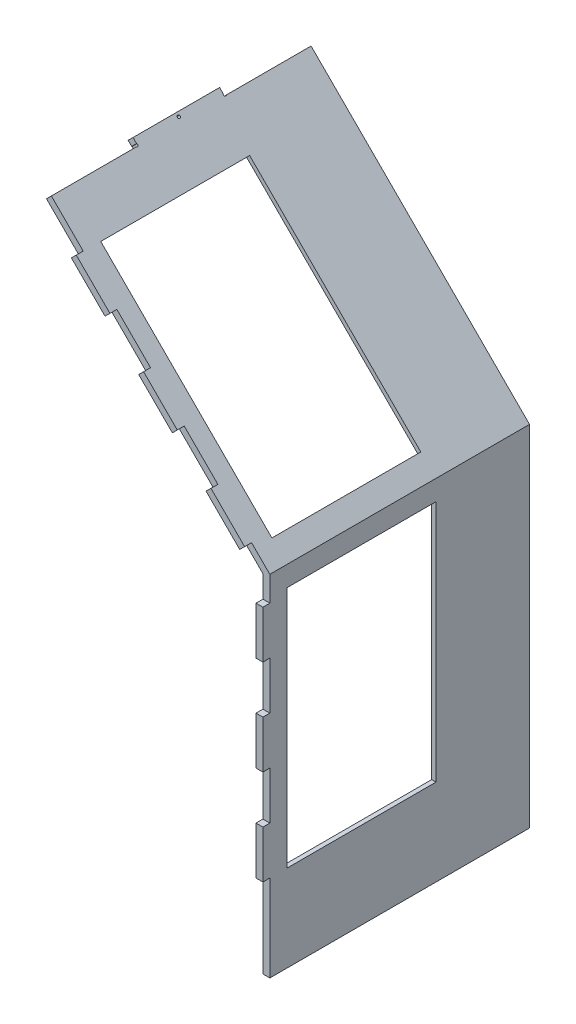
SolidWorks part; units mm, degrees
ref_plane "Plan de face" through (0, 0, 0) normal (0, 0, 1) x (1, 0, 0)
ref_plane "Plan de dessus" through (0, 0, 0) normal (0, 1, 0) x (1, 0, 0)
ref_plane "Plan de droite" through (0, 0, 0) normal (1, 0, 0) x (0, 0, -1)
sketch "Esquisse1" plane through (0, 0, 0) normal (0, 0, 1) x (1, 0, 0)
  line L0 (-190.432, 361.9326) -> (-44.5761, 361.9326) construction
  line L1 (-49.9708, -41.9174) -> (-57.9708, -41.9174)
  line L2 (-313.6277, 614.2758) -> (-307.9708, 619.9326)
  line L3 (-71.4129, -41.9174) -> (-190.432, -41.9174) construction
  line L4 (-57.9708, -41.9174) -> (-57.9708, 358.6189)
  line L6 (-57.9708, 358.6189) -> (-313.6277, 614.2758)
  line L11 (-49.9708, -41.9174) -> (-49.9708, 361.9326)
  line L13 (-49.9708, 361.9326) -> (-307.9708, 619.9326)
  dimension "D1" = 135
  dimension "D2" = 403.85
  dimension "D4" = 8
  dimension "D5" = 8
extrude "Boss.-Extru.1" add sketch "Esquisse1" along normal blind 308
sketch "Esquisse2" plane through (0, 0, 308) normal (0, 0, 1) x (1, 0, 0)
  line L0 (-57.9708, 358.6189) -> (-57.9708, -41.9174) construction
  line L1 (-57.9708, 58.0826) -> (-49.9708, 58.0826)
  line L2 (-57.9708, 58.0826) -> (-57.9708, -41.9174)
  line L3 (-57.9708, -41.9174) -> (-49.9708, -41.9174)
  line L4 (-49.9708, 58.0826) -> (-49.9708, -41.9174)
  line L5 (-57.9708, 223.0826) -> (-49.9708, 223.0826) construction
  line L6 (-49.9708, -41.9174) -> (-49.9708, 361.9326) construction
  line L7 (-57.9708, 168.0826) -> (-49.9708, 168.0826) construction
  line L8 (-57.9708, 278.0826) -> (-49.9708, 278.0826) construction
  line L9 (-57.9708, 333.0826) -> (-49.9708, 333.0826) construction
  line L10 (-57.9708, 113.0826) -> (-49.9708, 113.0826) construction
  line L11 (-271.2013, 571.8494) -> (-265.5444, 577.5062)
  line L12 (-57.9708, 168.0826) -> (-49.9708, 168.0826)
  line L13 (-57.9708, 168.0826) -> (-57.9708, 113.0826)
  line L14 (-57.9708, 113.0826) -> (-49.9708, 113.0826)
  line L15 (-49.9708, 168.0826) -> (-49.9708, 113.0826)
  line L16 (-57.9708, 278.0826) -> (-49.9708, 278.0826)
  line L17 (-57.9708, 278.0826) -> (-57.9708, 223.0826)
  line L18 (-57.9708, 223.0826) -> (-49.9708, 223.0826)
  line L19 (-49.9708, 278.0826) -> (-49.9708, 223.0826)
  line L21 (-313.6277, 614.2758) -> (-57.9708, 358.6189) construction
  line L23 (-232.3104, 532.9585) -> (-226.6535, 538.6153)
  line L24 (-193.4195, 494.0676) -> (-187.7627, 499.7245)
  line L25 (-154.5286, 455.1767) -> (-148.8718, 460.8336)
  line L26 (-115.6378, 416.2859) -> (-109.9809, 421.9427)
  line L27 (-76.7469, 377.395) -> (-71.09, 383.0518)
  line L28 (-307.9708, 619.9326) -> (-313.6277, 614.2758) construction
  line L29 (-49.9708, 361.9326) -> (-307.9708, 619.9326) construction
  line L30 (-271.2013, 571.8494) -> (-313.6277, 614.2758)
  line L31 (-313.6277, 614.2758) -> (-307.9708, 619.9326)
  line L32 (-307.9708, 619.9326) -> (-265.5444, 577.5062)
  line L33 (-193.4195, 494.0676) -> (-232.3104, 532.9585)
  line L34 (-226.6535, 538.6153) -> (-187.7627, 499.7245)
  line L35 (-154.5286, 455.1767) -> (-115.6378, 416.2859)
  line L36 (-148.8718, 460.8336) -> (-109.9809, 421.9427)
  line L37 (-76.7469, 377.395) -> (-57.9708, 358.6189)
  line L38 (-57.9708, 358.6189) -> (-57.9708, 333.0826)
  line L39 (-57.9708, 333.0826) -> (-49.9708, 333.0826)
  line L40 (-49.9708, 333.0826) -> (-49.9708, 361.9326)
  line L41 (-49.9708, 361.9326) -> (-71.09, 383.0518)
  dimension "D1" = 100
  dimension "D2" = 55
  dimension "D3" = 55
  dimension "D4" = 55
  dimension "D5" = 55
  dimension "D6" = 55
  dimension "D7" = 60
  dimension "D8" = 55
  dimension "D9" = 55
  dimension "D10" = 55
  dimension "D11" = 55
  dimension "D12" = 55
extrude "Enlèv. mat.-Extru.1" cut sketch "Esquisse2" against normal blind 8
sketch "Esquisse3" plane through (-57.9708, 0, 0) normal (-1, 0, 0) x (0, 0, 1)
  line L0 (0, 358.6189) -> (0, -41.9174) construction
  line L1 (108, 338.6189) -> (280, 338.6189)
  line L2 (108, 338.6189) -> (108, 58.0826)
  line L3 (108, 58.0826) -> (280, 58.0826)
  line L4 (280, 338.6189) -> (280, 58.0826)
  line L5 (300, -41.9174) -> (0, -41.9174) construction
  line L6 (308, 113.0826) -> (308, 58.0826) construction
  line L7 (300, 358.6189) -> (0, 358.6189) construction
  point P4 (0, 158.3508)
  dimension "D1" = 108
  dimension "D2" = 100
  dimension "D3" = 28
  dimension "D4" = 20
extrude "Enlèv. mat.-Extru.2" cut sketch "Esquisse3" against normal blind 532
sketch "Esquisse4" plane through (155.9809, 155.9809, 0) normal (0.7071, 0.7071, 0) x (0, 0, -1)
  line L0 (-280, 303.4015) -> (-280, 672.7468) construction
  line L1 (-311.171, 596.1268) -> (-51.2666, 596.1268) construction
  line L2 (-289.7557, 316.1268) -> (-51.2666, 316.1268) construction
  line L3 (-108, 303.4015) -> (-108, 641.5061) construction
  line L4 (-200, 648.1268) -> (-209.5238, 657.6506) construction
  line L5 (-225.5096, 648.1268) -> (-64.8946, 648.1268) construction
  line L6 (-200, 641.5061) -> (-200, 675.7701) construction
  line L7 (-250, 641.5061) -> (-250, 675.7701) construction
  line L8 (-168.9818, 652.1268) -> (-148.8675, 652.1268) construction
  line L9 (-300, 656.1268) -> (0, 656.1268) construction
  line L11 (-308, 541.1268) -> (-308, 596.1268) construction
  line L12 (-150, 675.7701) -> (-150, 641.5061) construction
  line L13 (-202.2627, 648.1268) -> (-300, 648.1268)
  line L14 (-300, 596.1268) -> (-300, 656.1268) construction
  line L15 (-300, 648.1268) -> (-300, 656.1268)
  line L16 (-300, 656.1268) -> (-200, 656.1268)
  line L17 (-200, 656.1268) -> (-200, 650.3896)
  line L18 (-100, 656.1268) -> (-100, 650.3896)
  line L19 (-97.7373, 648.1268) -> (0, 648.1268)
  line L20 (0, 656.1268) -> (-100, 656.1268)
  line L21 (0, 648.1268) -> (0, 656.1268)
  line L23 (-280, 595.7476) -> (-108, 595.7476)
  line L24 (-280, 595.7476) -> (-280, 316.1268)
  line L25 (-280, 316.1268) -> (-108, 316.1268)
  line L26 (-108, 595.7476) -> (-108, 316.1268)
  arc A0 (-202.2627, 648.1268) -> (-200, 650.3896) centre (-201.1314, 649.2582) ccw
  circle A1 centre (-150, 652.1268) radius 1.6
  arc A2 (-97.7373, 648.1268) -> (-100, 650.3896) centre (-98.8686, 649.2582) cw
  dimension "D7" = 4
  dimension "D8" = 60
  dimension "D1" = 8
  dimension "D2" = 50
  dimension "D3" = 50
  dimension "D4" = 28
  dimension "D5" = 172
  dimension "D6" = 45
  dimension "D9" = 280
extrude "Enlèv. mat.-Extru.3" cut sketch "Esquisse4" against normal blind 8
sketch "Esquisse5" plane through (-57.9708, 0, 0) normal (-1, 0, 0) x (0, 0, 1)
  line L0 (108, 338.6189) -> (108, 58.0826) construction
  line L1 (103, 343.6189) -> (285, 343.6189)
  line L2 (103, 343.6189) -> (103, 53.0826)
  line L3 (103, 53.0826) -> (285, 53.0826)
  line L4 (285, 343.6189) -> (285, 53.0826)
  line L5 (280, 338.6189) -> (108, 338.6189) construction
  dimension "D1" = 5
  dimension "D2" = 5
extrude "Enlèv. mat.-Extru.4" cut sketch "Esquisse5" against normal blind 3
sketch "Esquisse6" plane through (150.324, 150.324, 0) normal (-0.7071, -0.7071, 0) x (0, 0, 1)
  line L0 (108, 316.1268) -> (108, 595.7476) construction
  line L1 (103, 600.7476) -> (285, 600.7476)
  line L2 (103, 600.7476) -> (103, 310.7476)
  line L3 (103, 310.7476) -> (285, 310.7476)
  line L4 (285, 600.7476) -> (285, 310.7476)
  line L5 (108, 595.7476) -> (280, 595.7476) construction
  dimension "D1" = 5
  dimension "D2" = 5
extrude "Enlèv. mat.-Extru.5" cut sketch "Esquisse6" against normal blind 3
sketch "Esquisse7" plane through (-57.9708, 0, 0) normal (-1, 0, 0) x (0, 0, 1)
  line L0 (20, -47.6279) -> (20, -17.6578) construction
  line L1 (-5.1874, -21.9174) -> (22.5314, -21.9174) construction
  line L2 (300, -41.9174) -> (0, -41.9174) construction
  line L3 (0, 358.6189) -> (0, -41.9174) construction
  circle A0 centre (20, -21.9174) radius 4
  dimension "D1" = 20
  dimension "D2" = 20
extrude "Enlèv. mat.-Extru.6" cut sketch "Esquisse7" against normal blind 5.3
sketch "Esquisse8" plane through (-57.9708, 0, 0) normal (-1, 0, 0) x (0, 0, 1)
  line L0 (90, -55.273) -> (90, 367.1541) construction
  line L1 (98.5, -55.273) -> (98.5, 367.1541) construction
  line L2 (90, -50.0375) -> (98.5, -50.0375) construction
  line L3 (0, 358.6189) -> (0, -41.9174) construction
  line L5 (90, -46.3406) -> (98.5, -46.3406)
  line L6 (90, -46.3406) -> (90, 360.3929)
  line L7 (90, 360.3929) -> (98.5, 360.3929)
  line L8 (98.5, -46.3406) -> (98.5, 360.3929)
  dimension "D1" = 8.5
  dimension "D2" = 90
extrude "Enlèv. mat.-Extru.7" cut sketch "Esquisse8" against normal blind 4
sketch "Esquisse9" plane through (150.324, 150.324, 0) normal (-0.7071, -0.7071, 0) x (0, 0, 1)
  line L0 (90, 276.698) -> (90, 666.1723) construction
  line L1 (90, 11.3515) -> (90, 294.5734) construction
  line L2 (98.5, 276.698) -> (98.5, 666.1723) construction
  line L3 (98.5, 8.5231) -> (98.5, 292.9994) construction
  line L5 (90, 652.4585) -> (98.5, 652.4585)
  line L6 (90, 652.4585) -> (90, 293.147)
  line L7 (90, 293.147) -> (98.5, 293.147)
  line L8 (98.5, 652.4585) -> (98.5, 293.147)
extrude "Enlèv. mat.-Extru.8" cut sketch "Esquisse9" against normal blind 4
